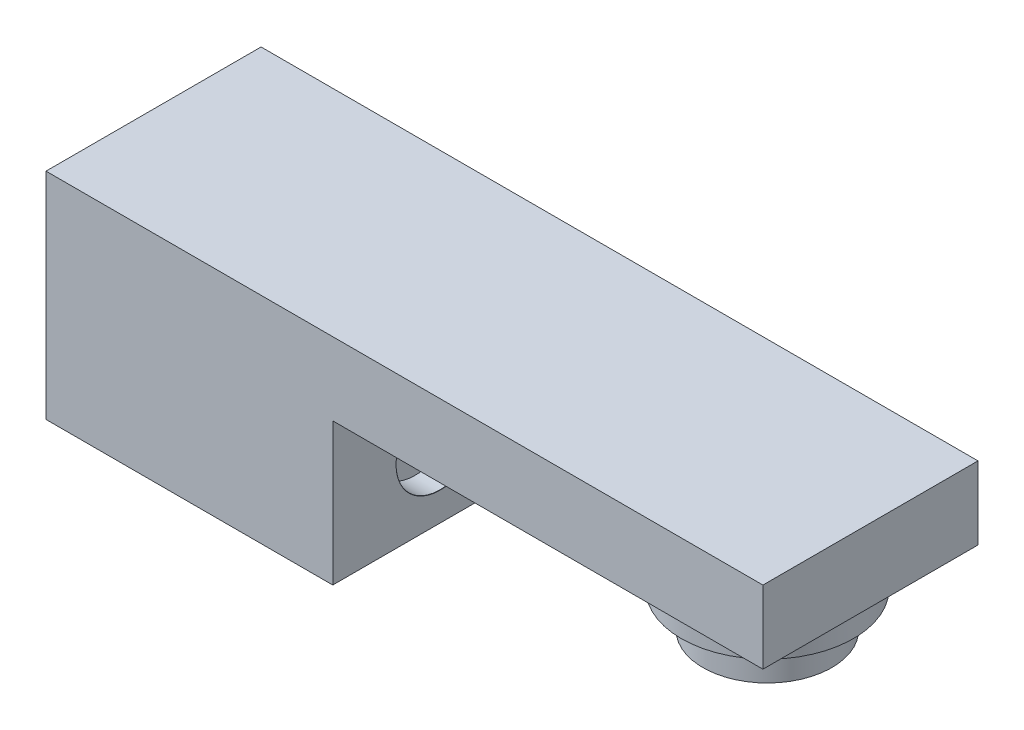
SolidWorks part; units mm, degrees
ref_plane "Спереди" through (0, 0, 0) normal (0, 0, 1) x (1, 0, 0)
ref_plane "Сверху" through (0, 0, 0) normal (0, 1, 0) x (1, 0, 0)
ref_plane "Справа" through (0, 0, 0) normal (1, 0, 0) x (0, 0, -1)
sketch "Эскиз1" plane through (0, 0, 0) normal (1, 0, 0) x (0, 0, -1)
  line L1 (-39.6578, -7.639) -> (-9.6578, -7.639)
  line L2 (-39.6578, -7.639) -> (-39.6578, 22.361)
  line L3 (-39.6578, 22.361) -> (-9.6578, 22.361)
  line L4 (-9.6578, -7.639) -> (-9.6578, 22.361)
extrude "Бобышка-Вытянуть1" add sketch "Эскиз1" along normal blind 40
sketch "Эскиз2" plane through (40, 0, 0) normal (1, 0, 0) x (0, 0, -1)
  line L0 (-24.6578, 22.361) -> (-24.6578, -9.226) construction
  line L1 (-9.6578, 22.361) -> (-39.6578, 22.361) construction
  line L2 (-9.6578, 7.361) -> (-46.9913, 7.361) construction
  line L3 (-9.6578, -7.639) -> (-9.6578, 22.361) construction
  line L4 (-46.9913, 12.1952) -> (-2.5903, 12.1952) construction
  line L6 (-39.6578, 22.361) -> (-9.6578, 22.361)
  line L7 (-39.6578, 22.361) -> (-39.6578, 12.1952)
  line L8 (-39.6578, 12.1952) -> (-9.6578, 12.1952)
  line L9 (-9.6578, 22.361) -> (-9.6578, 12.1952)
extrude "Бобышка-Вытянуть2" add sketch "Эскиз2" along normal blind 60
sketch "Эскиз3" plane through (0, 12.1952, 0) normal (0, -1, 0) x (1, 0, 0)
  line L0 (100, 24.6578) -> (37.0686, 24.6578) construction
  line L1 (100, 39.6578) -> (100, 9.6578) construction
  circle A0 centre (85.6202, 24.6578) radius 12
extrude "Бобышка-Вытянуть3" add sketch "Эскиз3" along normal blind 5
sketch "Эскиз4" plane through (0, 7.1952, 0) normal (0, -1, 0) x (1, 0, 0)
  line L0 (97.6202, 24.6578) -> (69.3301, 24.6578) construction
  line L1 (85.6202, 24.6578) -> (85.6202, 37.9572) construction
  circle A0 centre (85.6202, 24.6578) radius 12 construction
  circle A1 centre (85.6202, 24.6578) radius 12 construction
  circle A2 centre (85.6202, 24.6578) radius 9
extrude "Бобышка-Вытянуть4" add sketch "Эскиз4" along normal blind 5
hole_wizard "Цековка для  болта с шестигранной головкой M51" positions "Эскиз12" profile "Эскиз13" counterbore size "M5" standard "ISO" end condition through all
sketch "Эскиз12" plane through (40, 0, 0) normal (1, 0, 0) x (0, 0, -1)
  point P0 (-24.682, 2.4825)
sketch "Эскиз13" plane through (40, 2.4825, 24.682) normal (0, 1, 0) x (0, 0, -1)
  line L0 (0, 0) -> (0, 40)
  line L1 (0, 40) -> (2.75, 40)
  line L3 (2.75, 40) -> (2.75, 3.5)
  line L4 (6.119, 3.5) -> (2.75, 3.5)
  line L5 (6.119, 3.5) -> (6.119, 0.025)
  line L6 (6.119, 0.025) -> (6.144, 0)
  line L7 (6.144, 0) -> (0, 0)
  line L8 (-6.119, 0.025) -> (-6.144, 0) construction
  line L11 (0, -6.35) -> (0, 107.95) construction
  dimension "Диаметр сквозного отверстия" = 5.5
  dimension "Глубина сквозного отверстия" = 40
  dimension "Диаметр цековки" = 12.238
  dimension "Глубина цековки" = 3.5
  dimension "Диаметр передней зенковки" = 12.288
  dimension "Угол передней зенковки" = 90
